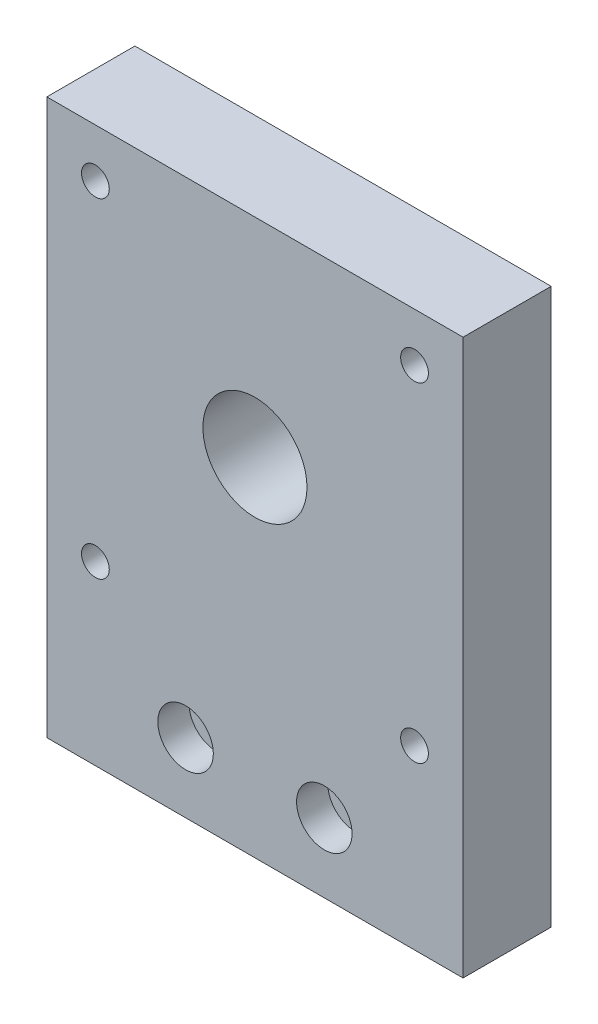
SolidWorks part; units mm, degrees
material "AISI 1035 Acero (SS)"
ref_plane "Alzado" through (0, 0, 0) normal (0, 0, 1) x (1, 0, 0)
ref_plane "Planta" through (0, 0, 0) normal (0, 1, 0) x (1, 0, 0)
ref_plane "Vista lateral" through (0, 0, 0) normal (1, 0, 0) x (0, 0, -1)
sketch "Croquis1" plane through (0, 0, 0) normal (0, 0, 1) x (1, 0, 0)
  line L0 (0, 0) -> (0, 61.5479) construction
  line L1 (-25.5, 40) -> (25.5, 40)
  line L2 (-28.5, 37) -> (-28.5, -40)
  line L3 (-28.5, -40) -> (28.5, -40)
  line L4 (28.5, 37) -> (28.5, -40)
  line L5 (-28.5, 40) -> (28.5, -40) construction
  line L6 (-28.5, -40) -> (28.5, 40) construction
  line L8 (25.5, 40) -> (30, 40)
  line L9 (25.5, 40) -> (25.5, -40)
  line L10 (25.5, -40) -> (30, -40)
  line L11 (30, 40) -> (30, -40)
  line L12 (-25.5, 40) -> (-30, 40)
  line L13 (-25.5, 40) -> (-25.5, -40)
  line L14 (-25.5, -40) -> (-30, -40)
  line L15 (-30, 40) -> (-30, -40)
  arc A0 (25.5, 40) -> (28.5, 37) centre (25.5, 37) cw
  arc A1 (-25.5, 40) -> (-28.5, 37) centre (-25.5, 37) ccw
  circle A2 centre (0, 10) radius 7.5
  circle A3 centre (10, -30) radius 2
  circle A4 centre (-10, -30) radius 2
  circle A5 centre (-23, 33) radius 2
  circle A6 centre (-23, -14.5) radius 2
  circle A7 centre (23, -14.5) radius 2
  circle A8 centre (23, 33) radius 2
  point P0 (0, 0)
  dimension "D3" = 3
  dimension "D5" = 15
  dimension "D11" = 4
  dimension "D1" = 80
  dimension "D2" = 57
  dimension "D6" = 10
  dimension "D7" = 20
  dimension "D8" = 10
  dimension "D4" = 50
  dimension "D9" = 5.5
  dimension "D10" = 7
  dimension "D12" = 47.5
  dimension "D13" = 80
  dimension "D15" = 80
  dimension "D14" = 60
  dimension "D16" = 30
extrude "Saliente-Extruir1" add sketch "Croquis1" along normal blind 12.7 contours A1 L12 L15 L14 L2 | L13 A1 L2 L3 | L1 L13 L3 L9 A7 A6 A5 A4 A3 A2 A8 | A0 L9 L3 L4 | L8 A0 L4 L10 L11
sketch "Croquis2" plane through (0, 0, 12.7) normal (0, 0, 1) x (1, 0, 0)
  circle A0 centre (-10, -30) radius 4
  circle A1 centre (10, -30) radius 4
extrude "Cortar-Extruir1" cut sketch "Croquis2" against normal blind 4.5
equation "\"D16@Croquis1\"=\"D14@Croquis1\"/2"
